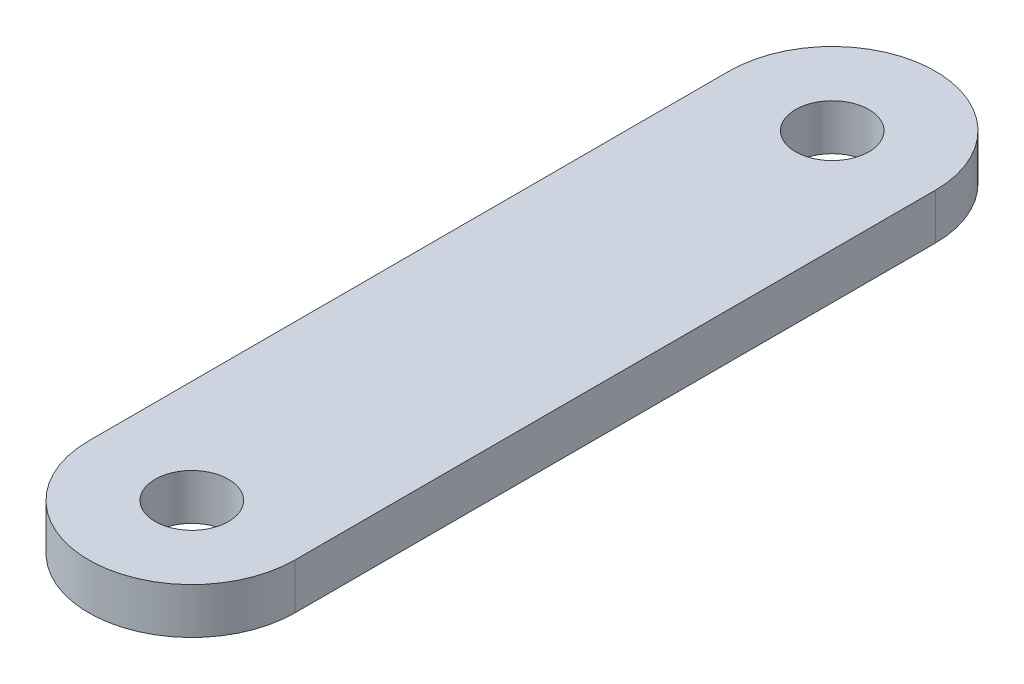
SolidWorks part; units mm, degrees
ref_plane "Front" through (0, 0, 0) normal (0, 0, 1) x (1, 0, 0)
ref_plane "Top" through (0, 0, 0) normal (0, 1, 0) x (1, 0, 0)
ref_plane "Right" through (0, 0, 0) normal (1, 0, 0) x (0, 0, -1)
sketch "Sketch1" plane through (0, 0, 0) normal (0, 1, 0) x (1, 0, 0)
  line L1 (-4.5, 0) -> (4.5, 0)
  line L2 (-4.5, 0) -> (-4.5, -27.94)
  line L3 (-4.5, -27.94) -> (4.5, -27.94)
  line L4 (4.5, 0) -> (4.5, -27.94)
  circle A0 centre (0, 0) radius 4.5
  circle A1 centre (0, -27.94) radius 4.5
  dimension "D1" = 27.94
  dimension "D2" = 9
  dimension "D3" = 9
extrude "Boss-Extrude1" add sketch "Sketch1" along normal blind 2 contours A1 L4 A0 L2 | L3 A1 | L3 A1
sketch "Sketch2" plane through (0, 2, 0) normal (0, 1, 0) x (1, 0, 0)
  circle A0 centre (0, 0) radius 1.6
  circle A1 centre (0, -27.94) radius 1.6
extrude "Cut-Extrude1" cut sketch "Sketch2" against normal blind 10
